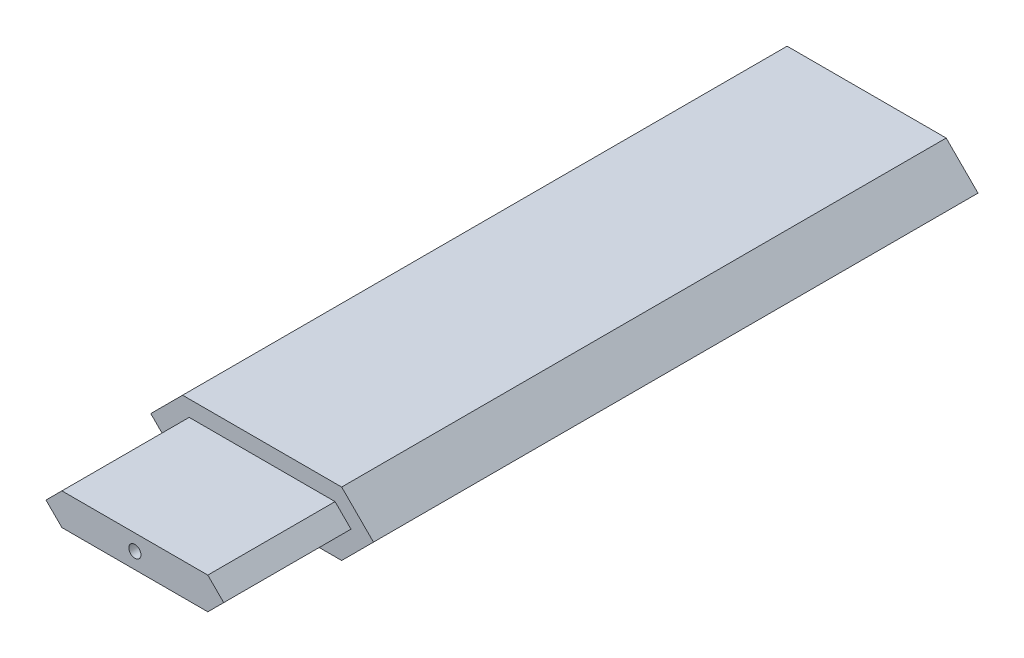
SolidWorks part; units mm, degrees
ref_plane "前视基准面" through (0, 0, 0) normal (0, 0, 1) x (1, 0, 0)
ref_plane "上视基准面" through (0, 0, 0) normal (0, 1, 0) x (1, 0, 0)
ref_plane "右视基准面" through (0, 0, 0) normal (1, 0, 0) x (0, 0, -1)
sketch "草图1" plane through (0, 0, 0) normal (0, 1, 0) x (1, 0, 0)
  line L0 (0, 0) -> (0, 690) construction
  line L1 (0, 690) -> (0, 630) construction
  line L2 (-35, 0) -> (35, 0)
  line L3 (-35, 0) -> (-35, 630)
  line L4 (-35, 630) -> (0, 690)
  line L5 (35, 630) -> (0, 690)
  line L6 (35, 0) -> (35, 630)
  dimension "D1" = 690
  dimension "D2" = 60
  dimension "D3" = 70
ref_plane "基准面1" through (0, 10, 0) normal (0, 1, 0) x (1, 0, 0)
sketch "草图4" plane through (0, 10, 0) normal (0, 1, 0) x (1, 0, 0)
  line L0 (25, 0) -> (-25, 0)
  line L1 (-25, 0) -> (-25, 630)
  line L2 (-25, 630) -> (0, 672.8571)
  line L3 (0, 0) -> (0, 690) construction
  line L4 (-35, 630) -> (0, 690) construction
  line L5 (0, -5.5) -> (0, 5.5) construction
  line L6 (25, 630) -> (0, 672.8571)
  line L7 (25, 0) -> (25, 630)
  point P2 (0, 0)
  dimension "D1" = 50
loft "放样1" add profiles "草图4", "草图1"
mirror "镜向1" about plane through (0, 0, 0) normal (0, 1, 0) of "放样1"
sketch "草图5" plane through (0, 0, 0) normal (0, 1, 0) x (1, 0, 0)
  line L0 (0, -30.5) -> (0, -55.5) construction
  line L1 (0, -55.5) -> (0, -30.5) construction
  line L2 (-79, -30.5) -> (79, -30.5) construction
  line L3 (0, -30.5) -> (0, 0) construction
  arc A0 (-66.3468, -65.1892) -> (66.3468, -65.1892) centre (0, -287.5) cw
  arc A1 (76.7912, -2.3877) -> (76.7912, -58.6123) centre (-101, -30.5) cw
  arc A2 (-76.7912, -2.3877) -> (-76.7912, -58.6123) centre (101, -30.5) ccw
  arc A4 (66.3468, -65.1892) -> (76.7912, -58.6123) centre (68.6918, -57.3316) ccw
  arc A5 (-66.3468, -65.1892) -> (-76.7912, -58.6123) centre (-68.6918, -57.3316) cw
  arc A6 (-76.7912, -2.3877) -> (76.7912, -2.3877) centre (0, 224.9955) ccw
  point P10 (0, -55.5)
  point P15 (79, -30.5)
  dimension "D4" = 232
  dimension "D5" = 180
  dimension "D6" = 8.2
  dimension "D7" = 240
  dimension "D1" = 25
  dimension "D2" = 158
  dimension "D3" = 30.5
extrude "凸台-拉伸1" add sketch "草图5" along normal mid plane 36 separate body
chamfer "倒角1" distance 5 angle 45 11 edges at (79, -18, 30.5) (73.0612, -18, 64.2705) (0, -18, 55.5) (-73.0612, -18, 64.2705) (-79, -18, 30.5) (79, 18, 30.5) (73.0612, 18, 64.2705) (0, 18, 55.5) (-73.0612, 18, 64.2705) (-79, 18, 30.5) (0, 18, 15.0045)
chamfer "倒角2" distance 5 angle 45 1 edges at (0, -18, 15.0045)
sketch "草图6" plane through (0, 18, 0) normal (0, 1, 0) x (1, 0, 0)
  arc A12 (67.2218, -55.0237) -> (68.3355, -15.4837) centre (-101, -30.5) ccw
  arc A13 (-68.3355, -15.4837) -> (68.3355, -15.4837) centre (0, 224.9955) ccw
  arc A14 (-68.3355, -15.4837) -> (-67.2218, -55.0237) centre (101, -30.5) ccw
  arc A15 (67.2218, -55.0237) -> (-67.2218, -55.0237) centre (0, -287.5) ccw
  arc A16 (67.2218, -55.0237) -> (68.3355, -15.4837) centre (-101, -30.5) ccw
  arc A17 (-68.3355, -15.4837) -> (68.3355, -15.4837) centre (0, 224.9955) ccw
  arc A18 (-68.3355, -15.4837) -> (-67.2218, -55.0237) centre (101, -30.5) ccw
  arc A19 (67.2218, -55.0237) -> (-67.2218, -55.0237) centre (0, -287.5) ccw
  dimension "D1" = 5
extrude "切除-拉伸1" cut sketch "草图6" against normal blind 8
mirror "镜向2" about plane through (0, 0, 0) normal (0, 1, 0) of "切除-拉伸1"
sketch "草图7" plane through (0, 0, 0) normal (0, 0, 1) x (1, 0, 0)
  line L12 (-25.8284, 12) -> (-37.8284, 0)
  line L13 (-37.8284, 0) -> (-25.8284, -12)
  line L14 (-25.8284, -12) -> (25.8284, -12)
  line L15 (25.8284, -12) -> (37.8284, 0)
  line L16 (37.8284, 0) -> (25.8284, 12)
  line L17 (25.8284, 12) -> (-25.8284, 12)
  line L18 (-25.8284, 12) -> (-37.8284, 0)
  line L19 (-37.8284, 0) -> (-25.8284, -12)
  line L20 (-25.8284, -12) -> (25.8284, -12)
  line L21 (25.8284, -12) -> (37.8284, 0)
  line L22 (37.8284, 0) -> (25.8284, 12)
  line L23 (25.8284, 12) -> (-25.8284, 12)
  dimension "D1" = 2
extrude "凸台-拉伸2" add sketch "草图7" along normal up to surface (12.0045 mm away)
sketch "草图8" plane through (0, 0, 0) normal (0, 0, -1) x (-1, 0, 0)
  line L6 (25.8284, 12) -> (-25.8284, 12)
  line L7 (-25.8284, 12) -> (-37.8284, 0)
  line L8 (-37.8284, 0) -> (-25.8284, -12)
  line L9 (-25.8284, -12) -> (25.8284, -12)
  line L10 (25.8284, -12) -> (37.8284, 0)
  line L11 (37.8284, 0) -> (25.8284, 12)
  line L12 (25.8284, 12) -> (-25.8284, 12)
  line L13 (-25.8284, 12) -> (-37.8284, 0)
  line L14 (-37.8284, 0) -> (-25.8284, -12)
  line L15 (-25.8284, -12) -> (25.8284, -12)
  line L16 (25.8284, -12) -> (37.8284, 0)
  line L17 (37.8284, 0) -> (25.8284, 12)
  dimension "D1" = 0
extrude "凸台-拉伸3" add sketch "草图8" along normal blind 5
sketch "草图9" plane through (0, 0, 0) normal (0, 1, 0) x (1, 0, 0)
  line L0 (0, 690) -> (0, -310) construction
  line L1 (0, -310) -> (0, -234)
  line L2 (0, -310) -> (0, -256) construction
  line L3 (-22.5, -256) -> (22.5, -256) construction
  line L4 (-22.5, -256) -> (0, -310)
  line L6 (-22.5, -256) -> (-12, -234)
  line L7 (-12, -234) -> (0, -234)
  dimension "D1" = 1000
  dimension "D2" = 76
  dimension "D3" = 54
  dimension "D4" = 45
  dimension "D5" = 12
revolve "旋转1" add sketch "草图9" angle 360 about L0
sketch "草图10" plane through (0, 0, 234) normal (0, 0, -1) x (-1, 0, 0)
  circle A1 centre (0, 0) radius 12
  circle A2 centre (0, 0) radius 12
  dimension "D1" = 0
extrude "凸台-拉伸4" add sketch "草图10" along normal up to next
sketch "草图16" plane through (0, 0, 0) normal (0, 1, 0) x (1, 0, 0)
  line L0 (0, 690) -> (0, -15.0045) construction
  line L1 (35, 630) -> (0, 690) construction
  line L2 (0, 0) -> (0, -20) construction
  line L3 (0, 5) -> (0, -35)
  line L4 (-50, 345) -> (50, 345)
  line L5 (-50, 345) -> (-50, 575)
  line L6 (-50, 575) -> (50, 575)
  line L7 (50, 345) -> (50, 575)
  line L8 (25.8284, 5) -> (-25.8284, 5) construction
  line L9 (0, -35) -> (0, 195)
  line L10 (0, 195) -> (0, 155)
  line L11 (0, 155) -> (0, 385)
  line L12 (0, 385) -> (0, 345)
  line L13 (0, 345) -> (0, 575)
  line L14 (0, 575) -> (0, 535)
  line L15 (0, 535) -> (0, 690)
  arc A0 (-25.8284, -13.6106) -> (25.8284, -13.6106) centre (0, 224.9955) ccw construction
  dimension "D7" = 40
  dimension "D1" = 40
  dimension "D2" = 20
  dimension "D3" = 100
  dimension "D4" = 230
  dimension "D5" = 40
  dimension "D6" = 230
  dimension "D8" = 230
  dimension "D9" = 40
extrude "切除-拉伸7" cut sketch "草图16" against normal through all both and the other way through all flip side to cut
sketch "草图21" plane through (0, 0, -345) normal (0, 0, 1) x (1, 0, 0)
  circle A0 centre (0, 0) radius 1.9
  dimension "D1" = 3.8
extrude "切除-拉伸17" cut sketch "草图21" against normal through all
sketch "草图34" plane through (0, 0, -345) normal (0, 0, 1) x (1, 0, 0)
  line L12 (-22.9289, -5) -> (22.9289, -5)
  line L13 (22.9289, -5) -> (27.9289, 0)
  line L14 (27.9289, 0) -> (22.9289, 5)
  line L15 (22.9289, 5) -> (-22.9289, 5)
  line L16 (-22.9289, 5) -> (-27.9289, 0)
  line L17 (-27.9289, 0) -> (-22.9289, -5)
  line L18 (-22.9289, -5) -> (22.9289, -5)
  line L19 (22.9289, -5) -> (27.9289, 0)
  line L20 (27.9289, 0) -> (22.9289, 5)
  line L21 (22.9289, 5) -> (-22.9289, 5)
  line L22 (-22.9289, 5) -> (-27.9289, 0)
  line L23 (-27.9289, 0) -> (-22.9289, -5)
  dimension "D1" = 5
extrude "切除-拉伸18" cut sketch "草图34" against normal blind 40 flip side to cut
sketch "草图35" plane through (0, 0, -575) normal (0, 0, -1) x (-1, 0, 0)
  line L12 (-28.2118, 0) -> (-23.0118, -5.2)
  line L13 (-23.0118, -5.2) -> (23.0118, -5.2)
  line L14 (23.0118, -5.2) -> (28.2118, 0)
  line L15 (28.2118, 0) -> (23.0118, 5.2)
  line L16 (23.0118, 5.2) -> (-23.0118, 5.2)
  line L17 (-23.0118, 5.2) -> (-28.2118, 0)
  line L18 (-28.2118, 0) -> (-23.0118, -5.2)
  line L19 (-23.0118, -5.2) -> (23.0118, -5.2)
  line L20 (23.0118, -5.2) -> (28.2118, 0)
  line L21 (28.2118, 0) -> (23.0118, 5.2)
  line L22 (23.0118, 5.2) -> (-23.0118, 5.2)
  line L23 (-23.0118, 5.2) -> (-28.2118, 0)
  dimension "D1" = 4.8
extrude "切除-拉伸19" cut sketch "草图35" against normal blind 41
